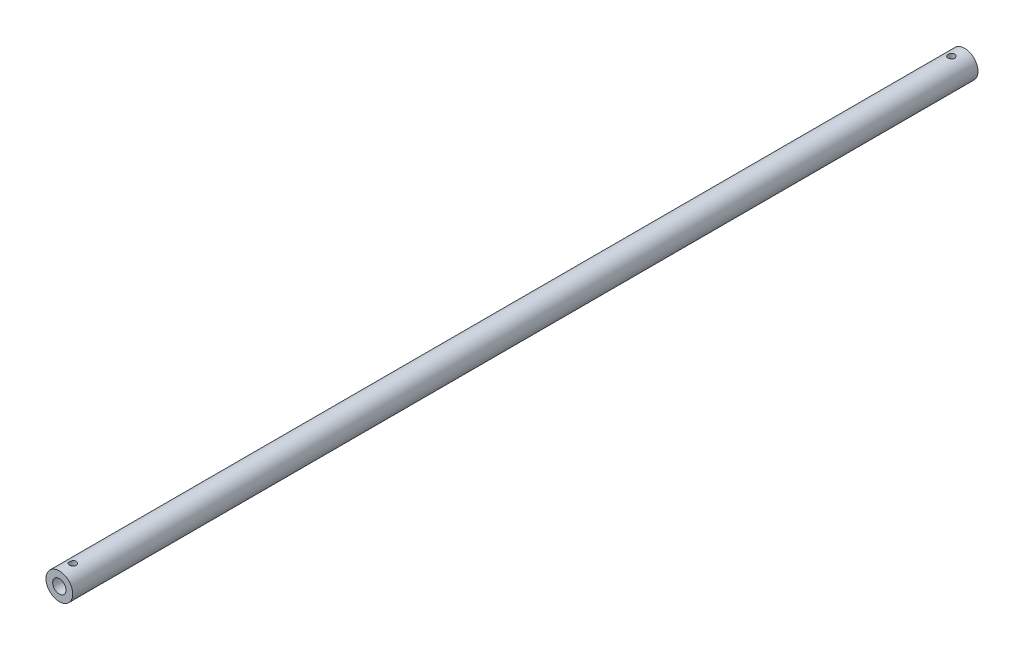
SolidWorks part; units mm, degrees
ref_plane "Front Plane" through (0, 0, 0) normal (0, 0, 1) x (1, 0, 0)
ref_plane "Top Plane" through (0, 0, 0) normal (0, 1, 0) x (1, 0, 0)
ref_plane "Right Plane" through (0, 0, 0) normal (1, 0, 0) x (0, 0, -1)
sketch "Sketch1" plane through (0, 0, 0) normal (0, 0, 1) x (1, 0, 0)
  circle A0 centre (0, 0) radius 10
  circle A1 centre (0, 0) radius 5
  dimension "D1" = 20
  dimension "D2" = 10
extrude "Boss-Extrude1" add sketch "Sketch1" along normal mid plane 677
sketch "Sketch2" plane through (0, 0, 0) normal (0, 1, 0) x (1, 0, 0)
  line L0 (-10, 0) -> (10, 0) construction
  line L1 (-10, 338.5) -> (-10, -338.5) construction
  line L2 (10, -338.5) -> (10, 338.5) construction
  line L3 (10, 338.5) -> (-10, 338.5) construction
  circle A0 centre (0, -328.5) radius 2.5
  circle A1 centre (0, 328.5) radius 2.5
  dimension "D1" = 5
  dimension "D2" = 10
extrude "Cut-Extrude1" cut sketch "Sketch2" against normal through all and the other way through all
ref_plane "Plane1" through (0, 0, 0) normal (0, 0, 1) x (1, 0, 0)
